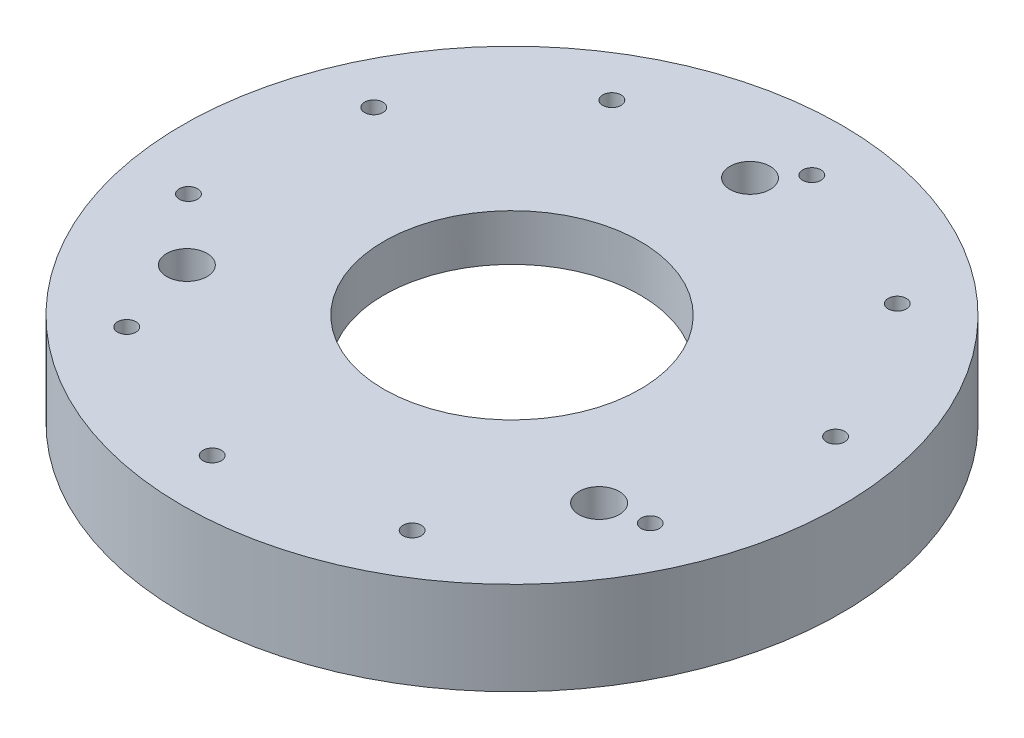
SolidWorks part; units mm, degrees
ref_plane "Front Plane" through (0, 0, 0) normal (0, 0, 1) x (1, 0, 0)
ref_plane "Top Plane" through (0, 0, 0) normal (0, 1, 0) x (1, 0, 0)
ref_plane "Right Plane" through (0, 0, 0) normal (1, 0, 0) x (0, 0, -1)
sketch "Sketch1" plane through (0, 0, 0) normal (0, 1, 0) x (1, 0, 0)
  line L0 (-36.436, -7.7447) -> (0, 0) construction
  line L1 (-28.1458, -16.25) -> (0, 0) construction
  circle A0 centre (0, 0) radius 45
  circle A1 centre (0, 32.5) radius 2.75
  circle A2 centre (0, 0) radius 32.5 construction
  circle A3 centre (28.1458, -16.25) radius 2.75
  circle A4 centre (-28.1458, -16.25) radius 2.75
  circle A5 centre (0, 0) radius 37.25 construction
  circle A6 centre (-36.436, -7.7447) radius 1.25
  circle A7 centre (-34.0296, 15.1509) radius 1.25
  circle A8 centre (-18.625, 32.2594) radius 1.25
  circle A9 centre (3.8937, 37.0459) radius 1.25
  circle A10 centre (24.9251, 27.6821) radius 1.25
  circle A11 centre (36.436, 7.7447) radius 1.25
  circle A12 centre (34.0296, -15.1509) radius 1.25
  circle A13 centre (18.625, -32.2594) radius 1.25
  circle A14 centre (-3.8937, -37.0459) radius 1.25
  circle A15 centre (-24.9251, -27.6821) radius 1.25
  circle A16 centre (0, 32.5) radius 4.25 construction
  circle A17 centre (28.1458, -16.25) radius 4.25 construction
  circle A18 centre (-28.1458, -16.25) radius 4.25 construction
  point P12 (0, 0)
  point P34 (0, 0)
  point P41 (0, 0)
  dimension "D1" = 90
  dimension "D2" = 65
  dimension "D3" = 5.5
  dimension "D5" = 74.5
  dimension "D6" = 2.5
  dimension "D9" = 8.5
  dimension "D7" = 18
  dimension "D4" = 3
  dimension "D8" = 10
  dimension "D10" = 3
extrude "Boss-Extrude1" add sketch "Sketch1" along normal blind 12.7
sketch "Sketch2" plane through (0, 12.7, 0) normal (0, 1, 0) x (1, 0, 0)
  circle A0 centre (0, 0) radius 17.5
  dimension "D1" = 35
extrude "Cut-Extrude1" cut sketch "Sketch2" against normal blind 6.35
sketch "Sketch3" plane through (0, 6.35, 0) normal (0, 1, 0) x (1, 0, 0)
  circle A0 centre (0, 0) radius 6
  dimension "D1" = 12
extrude "Cut-Extrude2" cut sketch "Sketch3" against normal through all
sketch "Sketch4" plane through (0, 0, 0) normal (0, -1, 0) x (1, 0, 0)
  circle A0 centre (0, 0) radius 28.5
  dimension "D1" = 57
extrude "Cut-Extrude3" cut sketch "Sketch4" against normal blind 6.35
sketch "Sketch6" plane through (0, 0, 0) normal (0, -1, 0) x (1, 0, 0)
  circle A0 centre (28.1458, 16.25) radius 4.25
  circle A1 centre (0, -32.5) radius 4.25
  circle A2 centre (-28.1458, 16.25) radius 4.25
  circle A3 centre (-28.1458, 16.25) radius 2.75 construction
  point P9 (0, 0)
  dimension "D1" = 8.5
  dimension "D2" = 3
extrude "Cut-Extrude4" cut sketch "Sketch6" against normal blind 6.35
